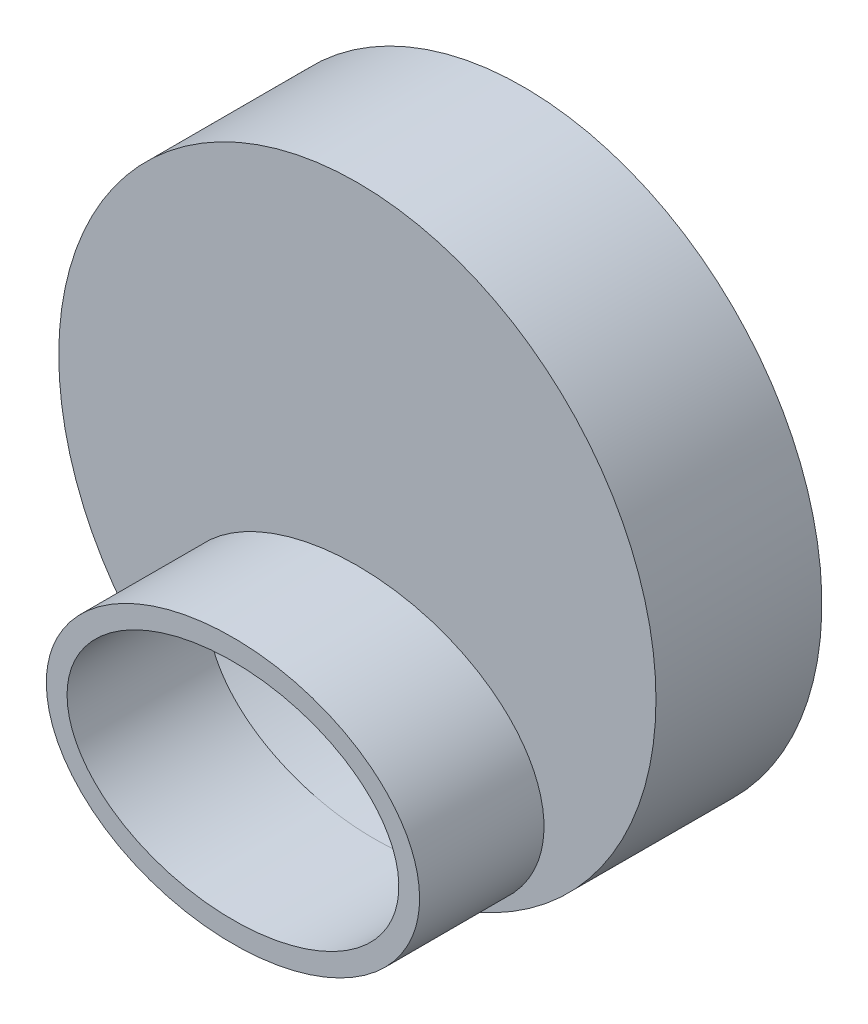
SolidWorks part; units mm, degrees
ref_plane "Alzado" through (0, 0, 0) normal (0, 0, 1) x (1, 0, 0)
ref_plane "Planta" through (0, 0, 0) normal (0, 1, 0) x (1, 0, 0)
ref_plane "Vista lateral" through (0, 0, 0) normal (1, 0, 0) x (0, 0, -1)
sketch "Croquis1" plane through (0, 0, 0) normal (0, 0, 1) x (1, 0, 0)
  circle A1 centre (0, 20) radius 28.2843 construction
  circle A2 centre (0, 20) radius 36
  ellipse E0 centre (0, 0) end of major axis (-20, 0) minor radius 13.5
  dimension "D4" = 72
  dimension "D1" = 40
  dimension "D2" = 27
  dimension "D3" = 20
extrude "Saliente-Extruir1" add sketch "Croquis1" along normal blind 2
sketch "Croquis2" plane through (0, 0, 2) normal (0, 0, 1) x (1, 0, 0)
  circle A0 centre (0, 20) radius 36 construction
  ellipse E1 centre (0, 0) end of major axis (-22.5, 0) minor radius 16
  ellipse E2 centre (0, 0) end of major axis (-20, 0) minor radius 13.5
  ellipse E3 centre (0, 0) end of major axis (-20, 0) minor radius 13.5
  dimension "D2" = 2.5
  dimension "D1" = 0
extrude "Saliente-Extruir2" add sketch "Croquis2" along normal blind 15
sketch "Croquis3" plane through (0, 0, 0) normal (0, 0, -1) x (-1, 0, 0)
  circle A0 centre (0, 20) radius 36
  circle A1 centre (0, 20) radius 33.5
  circle A2 centre (0, 20) radius 36 construction
  ellipse E0 centre (0, 0) end of major axis (20, 0) minor radius 13.5 construction
extrude "Saliente-Extruir3" add sketch "Croquis3" along normal blind 18
